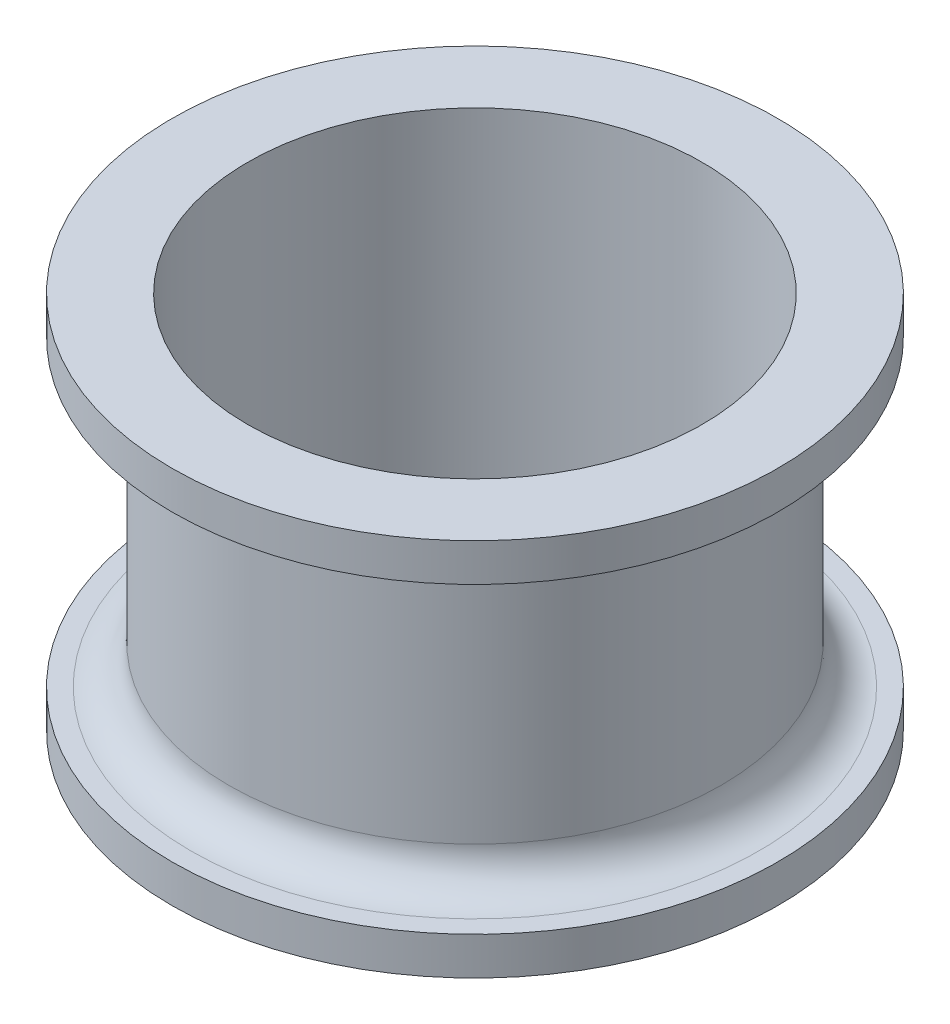
SolidWorks part; units mm, degrees
ref_plane "Front Plane" through (0, 0, 0) normal (0, 0, 1) x (1, 0, 0)
ref_plane "Top Plane" through (0, 0, 0) normal (0, 1, 0) x (1, 0, 0)
ref_plane "Right Plane" through (0, 0, 0) normal (1, 0, 0) x (0, 0, -1)
sketch "Sketch1" plane through (0, 0, 0) normal (0, 1, 0) x (1, 0, 0)
  circle A0 centre (0, 0) radius 6.5
  circle A1 centre (0, 0) radius 6
  dimension "D1" = 12
  dimension "D2" = 13
extrude "Boss-Extrude1" add sketch "Sketch1" along normal blind 10
sketch "Sketch2" plane through (0, 10, 0) normal (0, 1, 0) x (1, 0, 0)
  circle A0 centre (0, 0) radius 8
  circle A1 centre (0, 0) radius 6
  dimension "D1" = 16
extrude "Boss-Extrude2" add sketch "Sketch2" against normal blind 1
pattern_linear "LPattern1" count 2 spacing 9 along (0, -1, 0) of "Boss-Extrude2"
fillet "Fillet1" radius 1 2 edges at (0, 1, 6.5) (0, 9, 6.5)
